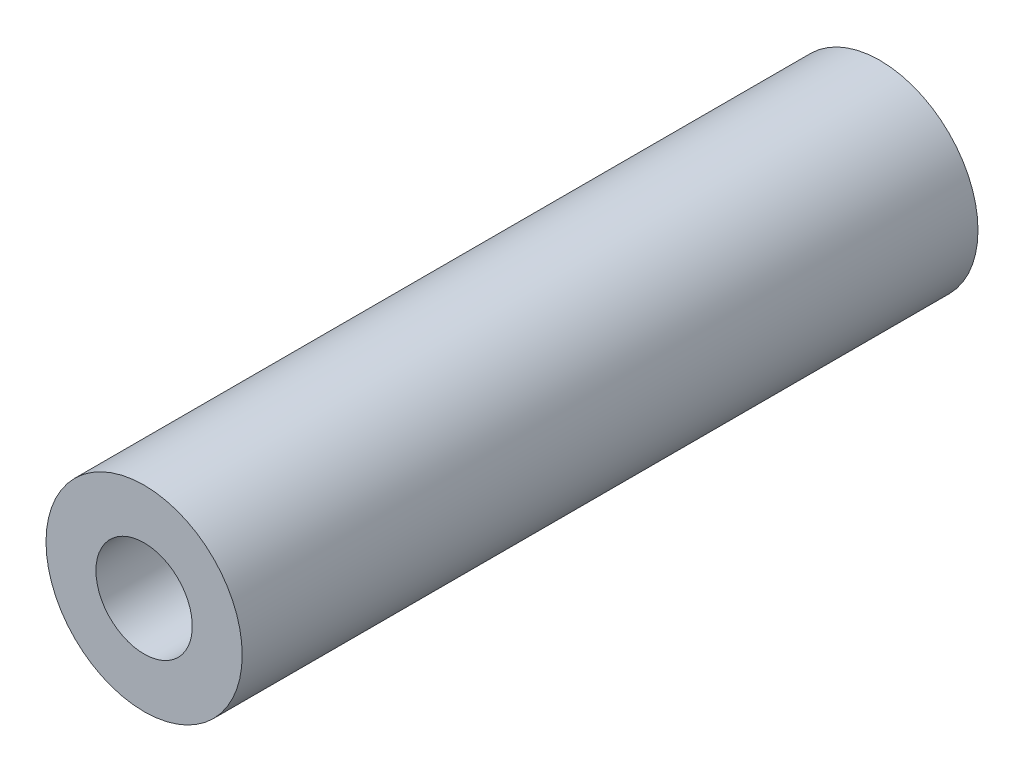
SolidWorks part; units mm, degrees
ref_plane "Front Plane" through (0, 0, 0) normal (0, 0, 1) x (1, 0, 0)
ref_plane "Top Plane" through (0, 0, 0) normal (0, 1, 0) x (1, 0, 0)
ref_plane "Right Plane" through (0, 0, 0) normal (1, 0, 0) x (0, 0, -1)
sketch "Sketch2" plane through (0, 0, 0) normal (0, 0, 1) x (1, 0, 0)
  circle A0 centre (0, 0) radius 5.08
  dimension "D1" = 10.16
extrude "Boss-Extrude1" add sketch "Sketch2" along normal blind 38.1
sketch "Sketch3" plane through (0, 0, 0) normal (0, 0, -1) x (-1, 0, 0)
  circle A0 centre (0, 0) radius 2.4948
extrude "Cut-Extrude1" cut sketch "Sketch3" against normal through all both and the other way through all
